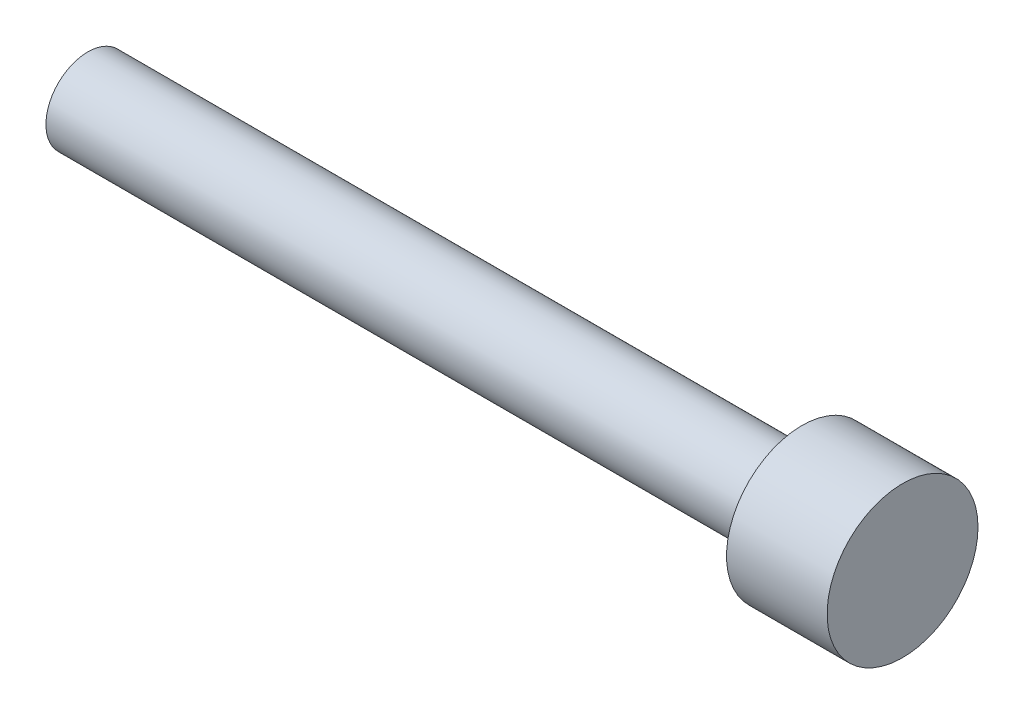
SolidWorks part; units mm, degrees
ref_plane "Front Plane" through (0, 0, 0) normal (0, 0, 1) x (1, 0, 0)
ref_plane "Top Plane" through (0, 0, 0) normal (0, 1, 0) x (1, 0, 0)
ref_plane "Right Plane" through (0, 0, 0) normal (1, 0, 0) x (0, 0, -1)
sketch "Sketch1" plane through (0, 0, 0) normal (1, 0, 0) x (0, 0, -1)
  circle A0 centre (0, 0) radius 1.25
  dimension "D1" = 2.5
extrude "Boss-Extrude1" add sketch "Sketch1" along normal mid plane 21.3
sketch "Sketch2" plane through (10.65, 0, 0) normal (1, 0, 0) x (0, 0, -1)
  circle A0 centre (0, 0) radius 2.25
  dimension "D1" = 4.5
extrude "Boss-Extrude2" add sketch "Sketch2" along normal blind 3
